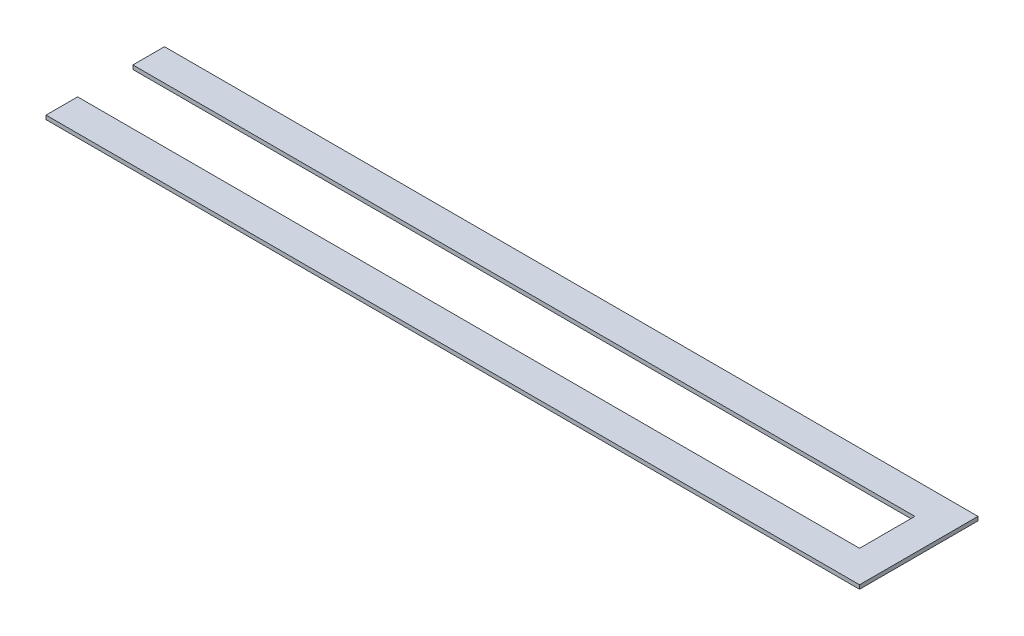
SolidWorks part; units mm, degrees
material "Copper"
ref_plane "Front Plane" through (0, 0, 0) normal (0, 0, 1) x (1, 0, 0)
ref_plane "Top Plane" through (0, 0, 0) normal (0, 1, 0) x (1, 0, 0)
ref_plane "Right Plane" through (0, 0, 0) normal (1, 0, 0) x (0, 0, -1)
sketch "Sketch7" plane through (0, 0, 0) normal (0, 1, 0) x (1, 0, 0)
  line L0 (-206, 22) -> (-206, 30)
  line L1 (0, 0) -> (-206, 0)
  line L2 (0, 0) -> (0, 30)
  line L3 (0, 30) -> (-206, 30)
  line L4 (-206, 0) -> (-206, 8)
  line L5 (0, 30) -> (-8, 30)
  line L6 (0, 30) -> (0, 0)
  line L7 (0, 0) -> (-8, 0)
  line L8 (-8, 22) -> (-8, 8)
  line L9 (-206, 30) -> (-8, 30)
  line L10 (-206, 30) -> (-206, 22)
  line L11 (-206, 22) -> (-8, 22)
  line L13 (-206, 0) -> (-8, 0)
  line L14 (-206, 0) -> (-206, 8)
  line L15 (-206, 8) -> (-8, 8)
  dimension "D1" = 30
  dimension "D2" = 206
  dimension "D3" = 14
  dimension "D4" = 8
  dimension "D5" = 8
  dimension "D6" = 8
extrude "Boss-Extrude1" add sketch "Sketch7" along normal blind 1 contours L15 L4 L1 L2 L3 L0 L11 L8
